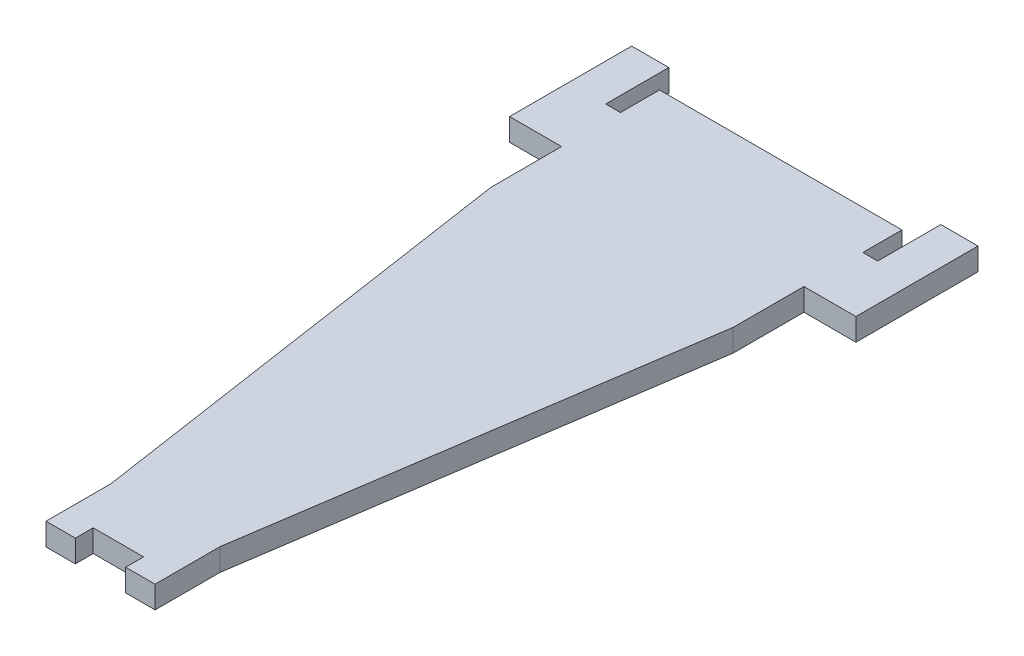
SolidWorks part; units mm, degrees
material "Actuator"
ref_plane "Front Plane" through (0, 0, 0) normal (0, 0, 1) x (1, 0, 0)
ref_plane "Top Plane" through (0, 0, 0) normal (0, 1, 0) x (1, 0, 0)
ref_plane "Right Plane" through (0, 0, 0) normal (1, 0, 0) x (0, 0, -1)
sketch "Sketch1" plane through (0, 0, 0) normal (0, 1, 0) x (1, 0, 0)
  line L0 (65.7711, 125.9985) -> (66.8161, 132.9985)
  line L1 (63.0161, 132.9985) -> (64.0611, 125.9985)
  line L2 (66.8161, 134.1085) -> (66.8161, 132.9985)
  line L3 (62.2012, 136.0226) -> (62.2012, 134.1085)
  line L4 (62.2012, 136.0226) -> (62.7836, 136.0226)
  line L5 (62.7836, 136.0226) -> (62.7836, 135.0319)
  line L6 (62.7836, 135.0319) -> (63.0161, 135.0319)
  line L7 (63.0161, 135.0319) -> (63.0161, 135.6447)
  line L8 (63.0161, 135.6447) -> (66.8161, 135.6447)
  line L9 (66.8161, 135.6447) -> (66.8161, 135.0319)
  line L10 (66.8161, 135.0319) -> (67.0486, 135.0319)
  line L11 (67.0486, 135.0319) -> (67.0486, 136.0226)
  line L12 (67.0486, 136.0226) -> (67.631, 136.0226)
  line L13 (67.631, 136.0226) -> (67.631, 134.1085)
  line L14 (66.8161, 134.1085) -> (67.631, 134.1085)
  line L15 (64.0611, 125.9985) -> (64.0611, 124.9801)
  line L16 (64.0611, 124.9801) -> (64.5211, 124.9801)
  line L17 (64.5211, 124.9801) -> (64.5211, 125.2601)
  line L18 (64.5211, 125.2601) -> (65.3111, 125.2601)
  line L19 (65.3111, 125.2601) -> (65.3111, 124.9801)
  line L20 (65.3111, 124.9801) -> (65.7711, 124.9801)
  line L21 (65.7711, 124.9801) -> (65.7711, 125.9985)
  line L22 (63.0161, 132.9985) -> (63.0161, 134.1085)
  line L23 (62.2012, 134.1085) -> (63.0161, 134.1085)
  point P1 (62.4924, 136.0226)
  point P2 (64.9161, 135.6447)
  point P27 (64.9161, 125.2601)
  dimension "D1" = 3.8
  dimension "D2" = 7
  dimension "D3" = 1.0184
  dimension "D4" = 1.11
  dimension "D5" = 0.8149
  dimension "D6" = 1.9141
  dimension "D7" = 0.9906
  dimension "D8" = 1.71
  dimension "D9" = 0.28
  dimension "D10" = 0.79
  dimension "D11" = 0.3778
extrude "Boss-Extrude1" add sketch "Sketch1" along normal blind 0.35
